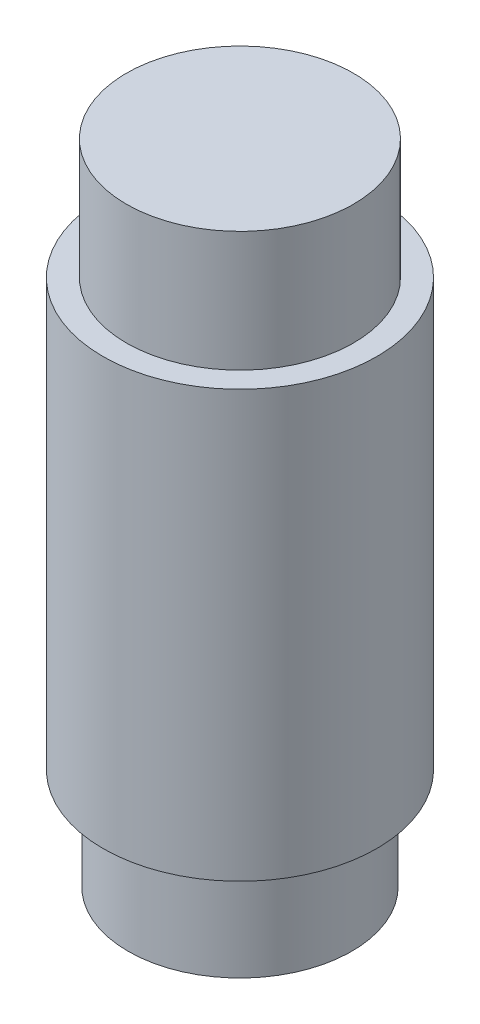
SolidWorks part; units mm, degrees
ref_plane "Plano frontal" through (0, 0, 0) normal (0, 0, 1) x (1, 0, 0)
ref_plane "Plano superior" through (0, 0, 0) normal (0, 1, 0) x (1, 0, 0)
ref_plane "Plano direito" through (0, 0, 0) normal (1, 0, 0) x (0, 0, -1)
sketch "Sketch1" plane through (0, 0, 0) normal (0, 1, 0) x (1, 0, 0)
  circle A0 centre (0, 0) radius 10.25
  dimension "D1" = 20.5
extrude "Boss-Extrude1" add sketch "Sketch1" along normal blind 31.9
sketch "Sketch2" plane through (0, 31.9, 0) normal (0, 1, 0) x (1, 0, 0)
  circle A0 centre (0, 0) radius 8.5
  dimension "D1" = 17
extrude "Boss-Extrude2" add sketch "Sketch2" along normal blind 4
sketch "Sketch3" plane through (0, 0, 0) normal (0, -1, 0) x (1, 0, 0)
  circle A0 centre (0, 0) radius 8.375
  dimension "D1" = 16.75
extrude "Boss-Extrude3" add sketch "Sketch3" along normal blind 7.6
sketch "Sketch6" plane through (0, 31.9, 0) normal (0, 1, 0) x (1, 0, 0)
  circle A0 centre (0, 0) radius 8.5
  dimension "D1" = 17
extrude "Boss-Extrude4" add sketch "Sketch6" along normal blind 9
